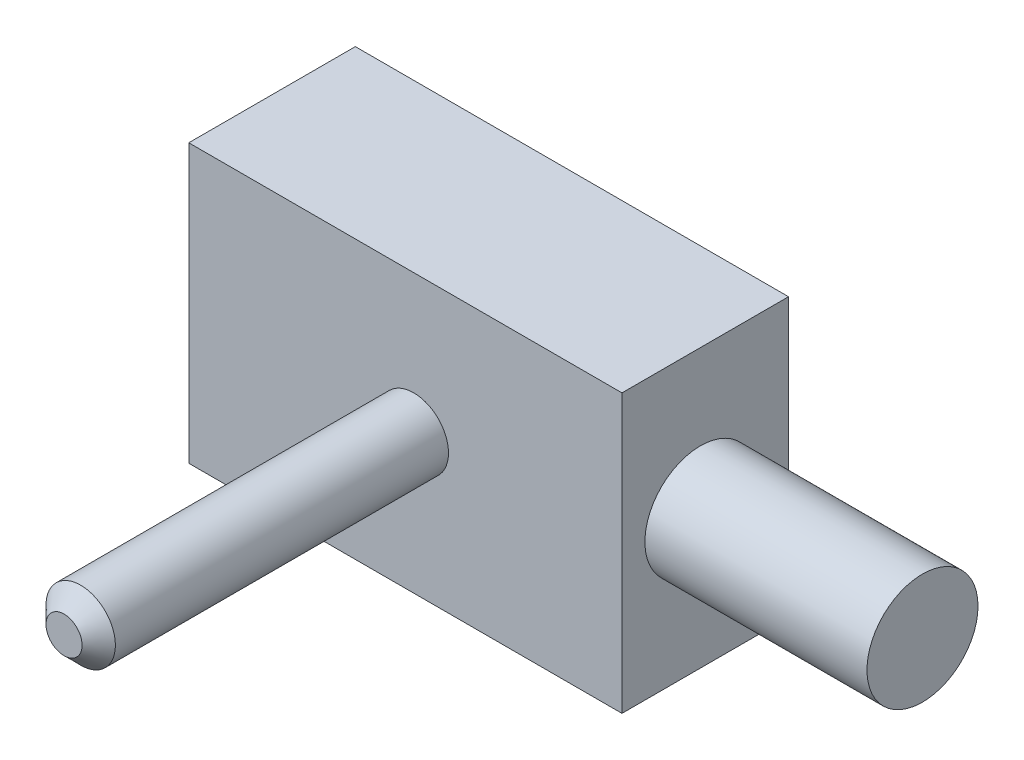
SolidWorks part; units mm, degrees
ref_plane "Front Plane" through (0, 0, 0) normal (0, 0, 1) x (1, 0, 0)
ref_plane "Top Plane" through (0, 0, 0) normal (0, 1, 0) x (1, 0, 0)
ref_plane "Right Plane" through (0, 0, 0) normal (1, 0, 0) x (0, 0, -1)
sketch "Sketch1" plane through (0, 0, 0) normal (0, 0, 1) x (1, 0, 0)
  line L1 (39.015, -25) -> (-39.015, -25)
  line L2 (39.015, -25) -> (39.015, 25)
  line L3 (39.015, 25) -> (-39.015, 25)
  line L4 (-39.015, -25) -> (-39.015, 25)
  point P0 (0, 0)
  dimension "D1" = 50
  dimension "D2" = 78.03
extrude "Boss-Extrude2" add sketch "Sketch1" along normal blind 30
sketch "Sketch2" plane through (39.015, 0, 0) normal (1, 0, 0) x (0, 0, -1)
  circle A0 centre (-15.87, -0.32) radius 10
extrude "Boss-Extrude3" add sketch "Sketch2" along normal blind 40
sketch "Sketch3" plane through (0, 0, 30) normal (0, 0, 1) x (1, 0, 0)
  circle A0 centre (1.515, 0) radius 6.25
extrude "Boss-Extrude8" add sketch "Sketch3" along normal blind 63
chamfer "Chamfer6" distance 3 angle 45 1 edges at (7.765, 0, 93)
